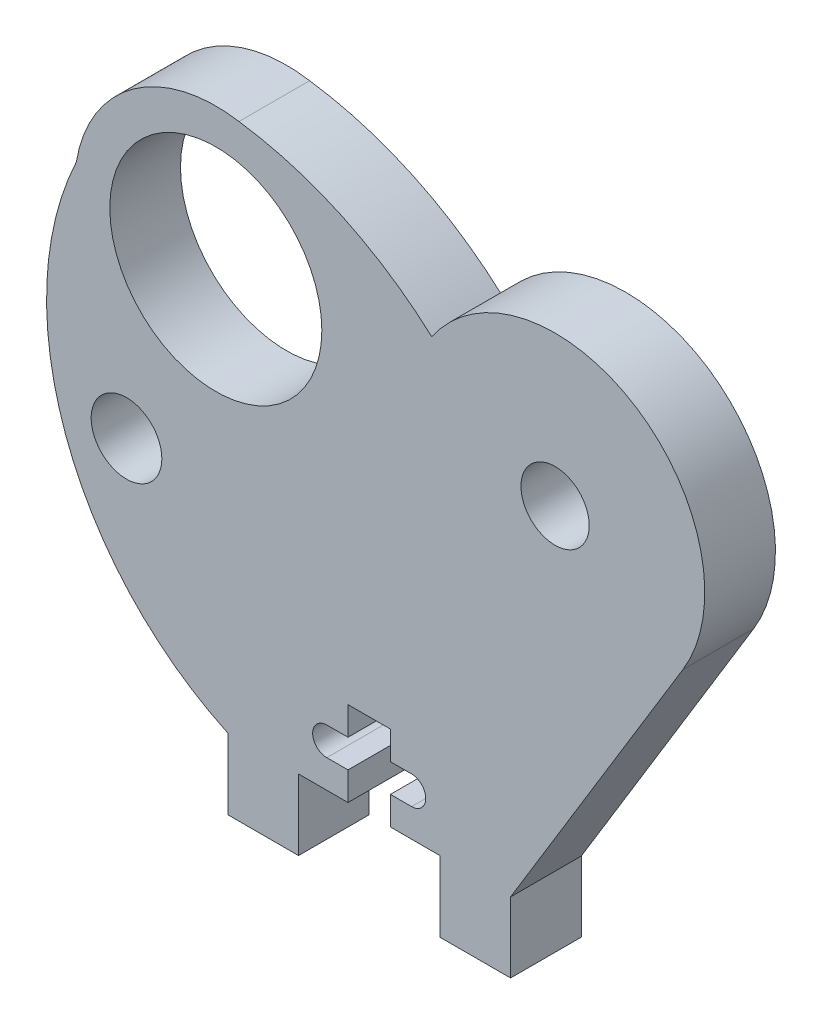
SolidWorks part; units mm, degrees
ref_plane "Front Plane" through (0, 0, 0) normal (0, 0, 1) x (1, 0, 0)
ref_plane "Top Plane" through (0, 0, 0) normal (0, 1, 0) x (1, 0, 0)
ref_plane "Right Plane" through (0, 0, 0) normal (1, 0, 0) x (0, 0, -1)
sketch "Sketch1" plane through (0, 0, 0) normal (0, 0, 1) x (1, 0, 0)
  line L0 (-1046.1481, -60.3978) -> (48953.8519, -60.3978) construction
  line L1 (-1091.4418, -10) -> (48908.5582, -10) construction
  line L4 (-64.1191, -48) -> (-60.6191, -48)
  line L5 (-80.7293, -20.5689) -> (-71.8483, -46.4784) construction
  line L6 (-68.798, -26.9702) -> (-48.7981, -26.9702) construction
  line L9 (-59.1191, -48) -> (-59.1191, -45) construction
  line L10 (-60.6191, -42) -> (-57.6191, -42)
  line L11 (-69.1191, -48) -> (-69.1191, -53)
  line L12 (-69.1191, -53) -> (-64.1191, -53)
  line L13 (-64.1191, -48) -> (-64.1191, -53)
  line L14 (-60.6191, -42) -> (-60.6191, -44)
  line L15 (-49.1191, -48.031) -> (-49.1191, -53)
  line L16 (-49.1191, -53) -> (-54.1191, -53)
  line L17 (-54.1191, -48) -> (-54.1191, -53)
  line L18 (-49.1191, -48.031) -> (-36.9264, -28.007)
  line L19 (-57.6191, -42) -> (-57.6191, -44)
  line L20 (-60.6191, -42) -> (-57.6191, -48) construction
  line L21 (-60.6191, -48) -> (-57.6191, -42) construction
  line L22 (-62.1191, -45) -> (-56.1191, -45) construction
  line L23 (-62.1191, -44) -> (-60.6191, -44)
  line L24 (-62.1191, -46) -> (-60.6191, -46)
  line L25 (-57.6191, -48) -> (-54.1191, -48)
  line L26 (-60.6191, -46) -> (-60.6191, -48)
  line L28 (-57.6191, -44) -> (-56.1191, -44)
  line L29 (-57.6191, -46) -> (-57.6191, -48)
  line L30 (-57.6191, -46) -> (-56.1191, -46)
  circle A0 centre (-91.9676, -38.8978) radius 21.5 construction
  circle A1 centre (-69.9705, -20) radius 7.5
  arc A2 (-69.9705, -20) -> (-58.7981, -26.9702) centre (-71.8379, -35.4323) cw construction
  arc A3 (-54.696, -16.5009) -> (-68.3342, -10.1348) centre (-71.8379, -35.4323) ccw
  circle A4 centre (-76.2888, -33.5236) radius 2.5
  arc A6 (-68.3342, -10.1348) -> (-79.8357, -18.3637) centre (-69.9705, -20) ccw
  arc A7 (-79.8357, -18.3637) -> (-69.1191, -48) centre (-59.6593, -27.8236) ccw
  arc A8 (-62.1191, -44) -> (-62.1191, -46) centre (-62.1191, -45) ccw
  arc A9 (-56.1191, -46) -> (-56.1191, -44) centre (-56.1191, -45) ccw
  arc A10 (-36.9264, -28.007) -> (-54.696, -16.5009) centre (-45.9705, -22.5) ccw
  circle A11 centre (-45.9705, -22.5) radius 2.4149
  point P23 (-63.7167, -22.52)
  point P37 (-59.1191, -45)
  point P46 (-59.1191, -45)
  dimension "D1" = 43
  dimension "D2" = 15
  dimension "D7" = 5
  dimension "D5" = 5
  dimension "D3" = 20
  dimension "D4" = 20
  dimension "D8" = 5
  dimension "D9" = 5
  dimension "D10" = 3
  dimension "D11" = 6
  dimension "D12" = 2
  dimension "D13" = 8
  dimension "D14" = 25
  dimension "D15" = 24
  dimension "D6" = 50.119
extrude "Boss-Extrude1" add sketch "Sketch1" along normal blind 5
